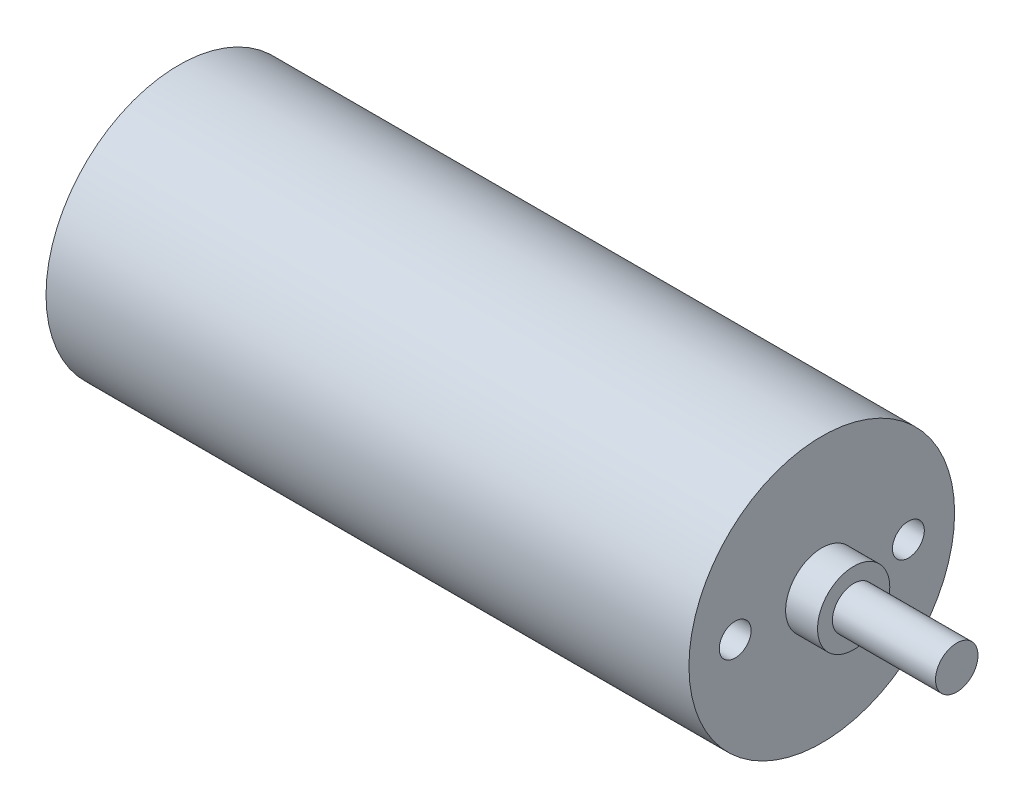
SolidWorks part; units mm, degrees
ref_plane "Front Plane" through (0, 0, 0) normal (0, 0, 1) x (1, 0, 0)
ref_plane "Top Plane" through (0, 0, 0) normal (0, 1, 0) x (1, 0, 0)
ref_plane "Right Plane" through (0, 0, 0) normal (1, 0, 0) x (0, 0, -1)
sketch "Sketch2" plane through (0, 0, 0) normal (0, 0, 1) x (1, 0, 0)
  line L0 (0, 0) -> (0, 12.5)
  line L1 (0, 12.5) -> (60.5, 12.5)
  line L2 (60.5, 12.5) -> (60.5, 3.4)
  line L3 (60.5, 3.4) -> (63.5, 3.4)
  line L4 (63.5, 3.4) -> (63.5, 2)
  line L5 (63.5, 2) -> (73.2, 2)
  line L6 (73.2, 2) -> (73.2, 0)
  line L7 (73.2, 0) -> (0, 0)
  dimension "D1" = 12.5
  dimension "D2" = 2
  dimension "D3" = 3.4
  dimension "D4" = 9.7
  dimension "D5" = 60.5
  dimension "D6" = 3
revolve "Revolve1" add sketch "Sketch2" angle 360 about L7
sketch "Sketch3" plane through (60.5, 0, 0) normal (1, 0, 0) x (0, 0, -1)
  line L0 (0, 12.5) -> (0, -12.5) construction
  circle A0 centre (8.15, 0) radius 1.5
  circle A1 centre (-8.15, 0) radius 1.5
  circle A2 centre (0, 0) radius 12.5 construction
  point P4 (0, 0)
  dimension "D2" = 3
  dimension "D1" = 16.3
extrude "Cut-Extrude1" cut sketch "Sketch3" against normal blind 3
